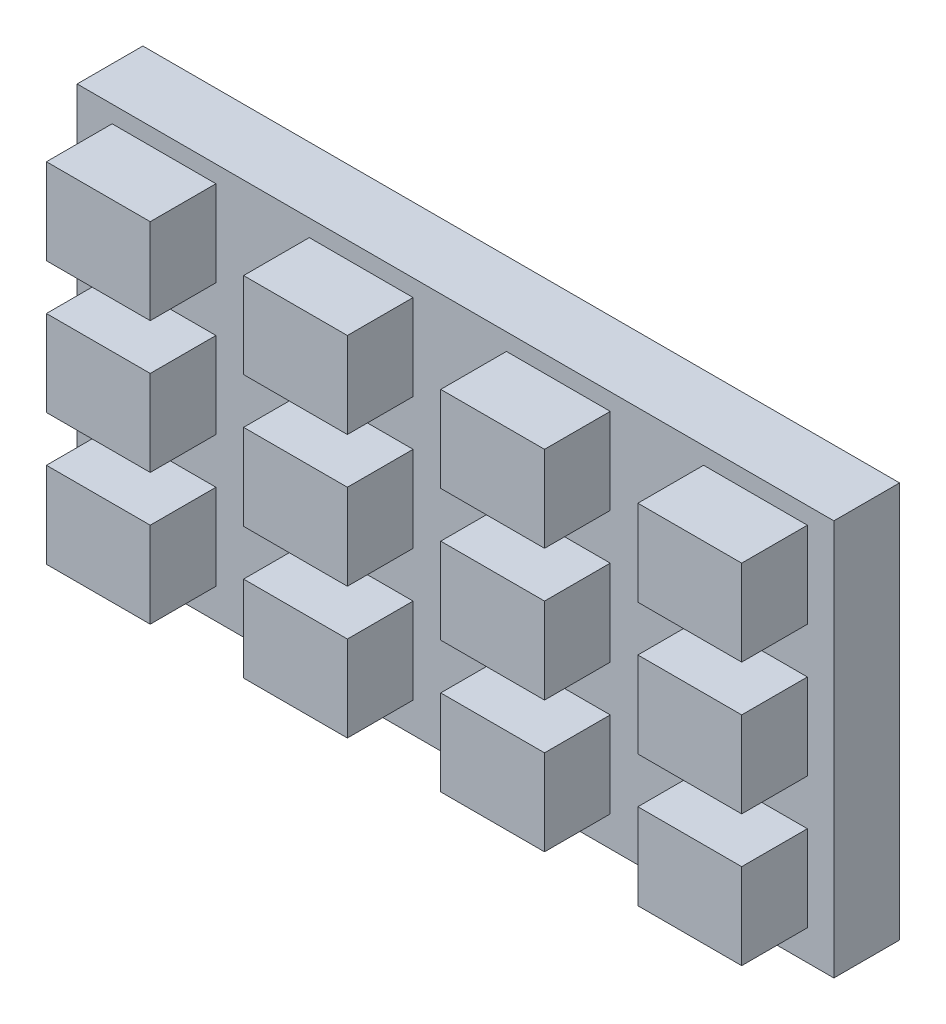
SolidWorks part; units mm, degrees
ref_plane "Front Plane" through (0, 0, 0) normal (0, 0, 1) x (1, 0, 0)
ref_plane "Top Plane" through (0, 0, 0) normal (0, 1, 0) x (1, 0, 0)
ref_plane "Right Plane" through (0, 0, 0) normal (1, 0, 0) x (0, 0, -1)
sketch "Sketch1" plane through (0, 0, 0) normal (0, 0, 1) x (1, 0, 0)
  line L0 (-16.7024, -15.6247) -> (-16.7024, -28.6739)
  line L1 (48.076, 34.5117) -> (-71.0838, 34.5117)
  line L2 (48.076, 34.5117) -> (48.076, -36.9155)
  line L3 (48.076, -36.9155) -> (-71.0838, -36.9155)
  line L4 (-71.0838, 34.5117) -> (-71.0838, -36.9155)
  line L5 (-46.7024, -15.6247) -> (-62.4988, -15.6247)
  line L6 (-46.7024, -15.6247) -> (-46.7024, -28.6739)
  line L7 (-46.7024, -28.6739) -> (-62.4988, -28.6739)
  line L8 (-62.4988, -15.6247) -> (-62.4988, -28.6739)
  line L9 (-16.7024, -15.6247) -> (-32.4988, -15.6247)
  line L10 (-32.4988, -15.6247) -> (-32.4988, -28.6739)
  line L11 (-16.7024, -28.6739) -> (-32.4988, -28.6739)
  line L12 (13.2976, -15.6247) -> (13.2976, -28.6739)
  line L13 (13.2976, -15.6247) -> (-2.4988, -15.6247)
  line L14 (-2.4988, -15.6247) -> (-2.4988, -28.6739)
  line L15 (13.2976, -28.6739) -> (-2.4988, -28.6739)
  line L16 (43.2976, -15.6247) -> (43.2976, -28.6739)
  line L17 (43.2976, -15.6247) -> (27.5012, -15.6247)
  line L18 (27.5012, -15.6247) -> (27.5012, -28.6739)
  line L19 (43.2976, -28.6739) -> (27.5012, -28.6739)
  line L20 (-16.7024, 4.3753) -> (-16.7024, -8.6739)
  line L21 (-16.7024, 4.3753) -> (-32.4988, 4.3753)
  line L22 (-32.4988, 4.3753) -> (-32.4988, -8.6739)
  line L23 (-16.7024, -8.6739) -> (-32.4988, -8.6739)
  line L24 (13.2976, 4.3753) -> (13.2976, -8.6739)
  line L25 (13.2976, 4.3753) -> (-2.4988, 4.3753)
  line L26 (-2.4988, 4.3753) -> (-2.4988, -8.6739)
  line L27 (13.2976, -8.6739) -> (-2.4988, -8.6739)
  line L28 (43.2976, 4.3753) -> (43.2976, -8.6739)
  line L29 (43.2976, 4.3753) -> (27.5012, 4.3753)
  line L30 (27.5012, 4.3753) -> (27.5012, -8.6739)
  line L31 (43.2976, -8.6739) -> (27.5012, -8.6739)
  line L32 (-16.7024, 24.3753) -> (-16.7024, 11.3261)
  line L33 (-16.7024, 24.3753) -> (-32.4988, 24.3753)
  line L34 (-32.4988, 24.3753) -> (-32.4988, 11.3261)
  line L35 (-16.7024, 11.3261) -> (-32.4988, 11.3261)
  line L36 (13.2976, 24.3753) -> (13.2976, 11.3261)
  line L37 (13.2976, 24.3753) -> (-2.4988, 24.3753)
  line L38 (-2.4988, 24.3753) -> (-2.4988, 11.3261)
  line L39 (13.2976, 11.3261) -> (-2.4988, 11.3261)
  line L40 (43.2976, 24.3753) -> (43.2976, 11.3261)
  line L41 (43.2976, 24.3753) -> (27.5012, 24.3753)
  line L42 (27.5012, 24.3753) -> (27.5012, 11.3261)
  line L43 (43.2976, 11.3261) -> (27.5012, 11.3261)
  line L44 (-46.7024, 4.3753) -> (-46.7024, -8.6739)
  line L45 (-46.7024, 4.3753) -> (-62.4988, 4.3753)
  line L46 (-62.4988, 4.3753) -> (-62.4988, -8.6739)
  line L47 (-46.7024, -8.6739) -> (-62.4988, -8.6739)
  line L48 (-46.7024, 24.3753) -> (-46.7024, 11.3261)
  line L49 (-46.7024, 24.3753) -> (-62.4988, 24.3753)
  line L50 (-62.4988, 24.3753) -> (-62.4988, 11.3261)
  line L51 (-46.7024, 11.3261) -> (-62.4988, 11.3261)
  point P8 (0, 0)
  point P9 (0, 0)
  point P54 (0, 0)
  dimension "D1" = 4
  dimension "D2" = 3
extrude "Boss-Extrude2" add sketch "Sketch1" along normal blind 10 contours L13 L14 L15 L12 | L9 L10 L11 L0 | L5 L8 L7 L6 | L17 L18 L19 L16 | L21 L22 L23 L20 | L25 L26 L27 L24 | L29 L30 L31 L28 | L45 L46 L47 L44 | L41 L42 L43 L40 | L37 L38 L39 L36 | L33 L34 L35 L32 | L49 L50 L51 L48
sketch "Sketch2" plane through (0, 0, 0) normal (0, 0, 1) x (1, 0, 0)
  line L1 (-67.8254, 26.9631) -> (47.3238, 26.9631)
  line L2 (-67.8254, 26.9631) -> (-67.8254, -33.2844)
  line L3 (-67.8254, -33.2844) -> (47.3238, -33.2844)
  line L4 (47.3238, 26.9631) -> (47.3238, -33.2844)
extrude "Boss-Extrude3" add sketch "Sketch2" against normal blind 10 contours L1 L4 L3 L2
